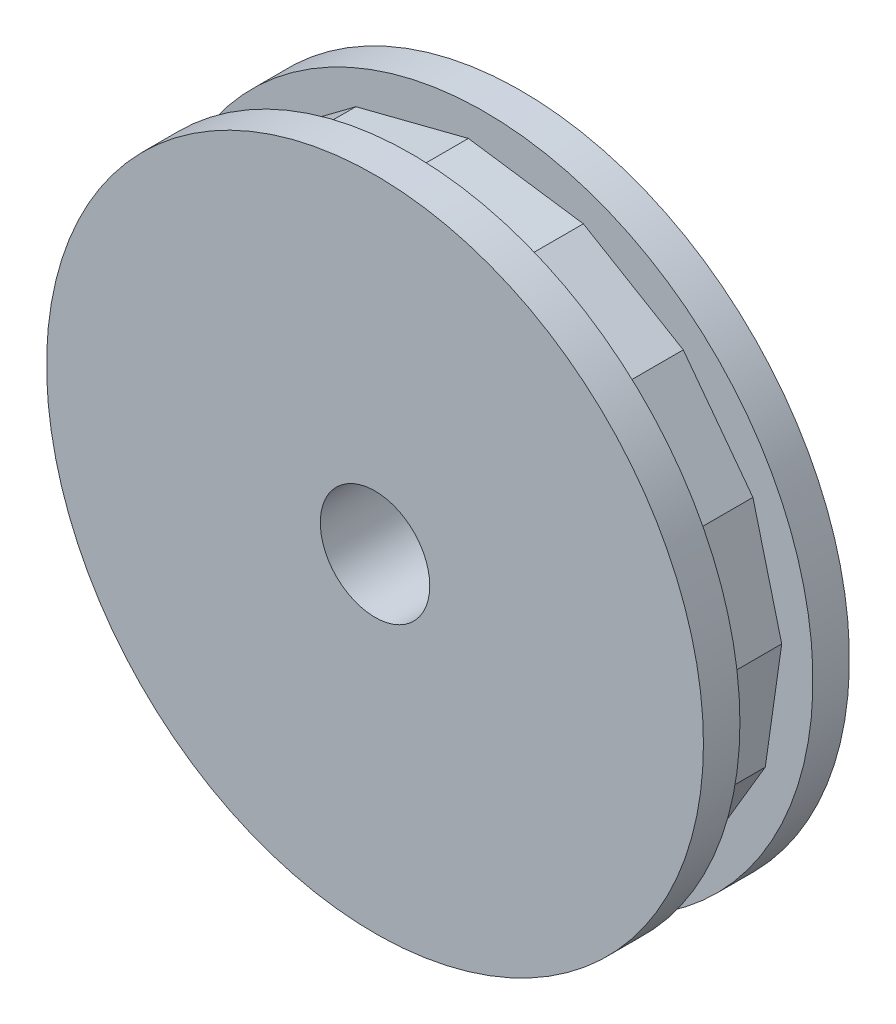
SolidWorks part; units mm, degrees
ref_plane "Спереди" through (0, 0, 0) normal (0, 0, 1) x (1, 0, 0)
ref_plane "Сверху" through (0, 0, 0) normal (0, 1, 0) x (1, 0, 0)
ref_plane "Справа" through (0, 0, 0) normal (1, 0, 0) x (0, 0, -1)
sketch "Эскиз1" plane through (0, 0, 0) normal (0, 0, 1) x (1, 0, 0)
  line L1 (8.1448, 0.4416) -> (7.3558, 3.5249)
  line L2 (7.3558, 3.5249) -> (5.447, 6.0715)
  line L3 (5.447, 6.0715) -> (2.7089, 7.6938)
  line L4 (2.7089, 7.6938) -> (-0.4416, 8.1448)
  line L5 (-0.4416, 8.1448) -> (-3.5249, 7.3558)
  line L6 (-3.5249, 7.3558) -> (-6.0715, 5.447)
  line L7 (-6.0715, 5.447) -> (-7.6938, 2.7089)
  line L8 (-7.6938, 2.7089) -> (-8.1448, -0.4416)
  line L9 (-8.1448, -0.4416) -> (-7.3558, -3.5249)
  line L10 (-7.3558, -3.5249) -> (-5.447, -6.0715)
  line L11 (-5.447, -6.0715) -> (-2.7089, -7.6938)
  line L12 (-2.7089, -7.6938) -> (0.4416, -8.1448)
  line L13 (0.4416, -8.1448) -> (3.5249, -7.3558)
  line L14 (3.5249, -7.3558) -> (6.0715, -5.447)
  line L15 (6.0715, -5.447) -> (7.6938, -2.7089)
  line L16 (7.6938, -2.7089) -> (8.1448, 0.4416)
  circle A0 centre (0, 0) radius 8 construction
extrude "Бобышка-Вытянуть1" add sketch "Эскиз1" along normal blind 2
sketch "Эскиз2" plane through (0, 0, 0) normal (0, 0, -1) x (-1, 0, 0)
  circle A0 centre (0, 0) radius 9
extrude "Бобышка-Вытянуть2" add sketch "Эскиз2" along normal blind 1
sketch "Эскиз3" plane through (0, 0, 2) normal (0, 0, 1) x (1, 0, 0)
  circle A0 centre (0, 0) radius 9
extrude "Бобышка-Вытянуть3" add sketch "Эскиз3" along normal blind 1
sketch "Эскиз4" plane through (0, 0, 3) normal (0, 0, 1) x (1, 0, 0)
  circle A0 centre (0, 0) radius 1.5
extrude "Вырез-Вытянуть1" cut sketch "Эскиз4" against normal through all
